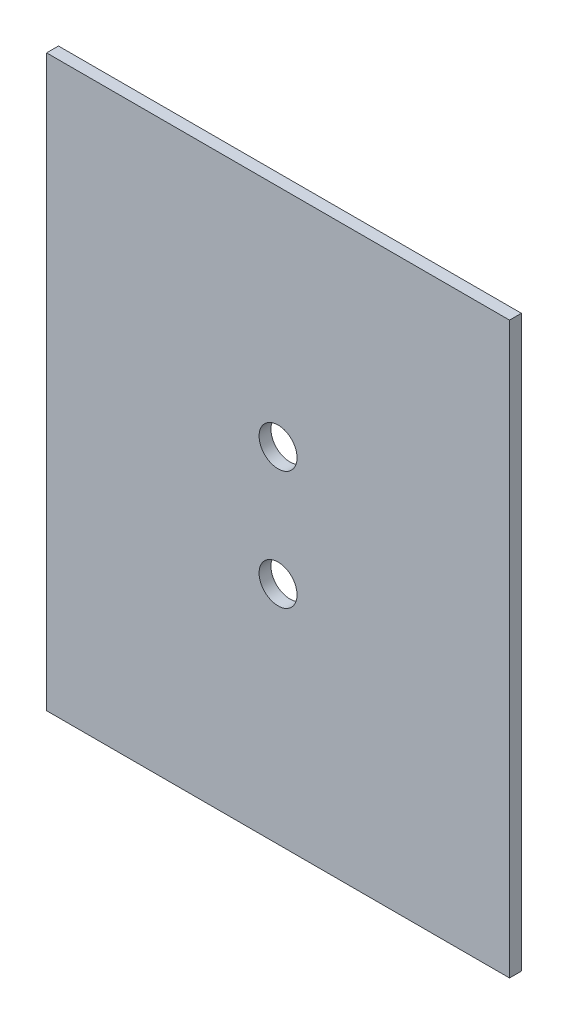
SolidWorks part; units mm, degrees
material "Pine"
ref_plane "Front Plane" through (0, 0, 0) normal (0, 0, 1) x (1, 0, 0)
ref_plane "Top Plane" through (0, 0, 0) normal (0, 1, 0) x (1, 0, 0)
ref_plane "Right Plane" through (0, 0, 0) normal (1, 0, 0) x (0, 0, -1)
sketch "Sketch1" plane through (0, 0, 0) normal (0, 0, 1) x (1, 0, 0)
  line L1 (-97.5, 120) -> (97.5, 120)
  line L2 (-97.5, 120) -> (-97.5, -120)
  line L3 (-97.5, -120) -> (97.5, -120)
  line L4 (97.5, 120) -> (97.5, -120)
  circle A0 centre (0, 25) radius 8
  circle A1 centre (0, -25) radius 8
  point P0 (0, 0)
  dimension "D3" = 16
  dimension "D1" = 195
  dimension "D2" = 240
  dimension "D4" = 50
extrude "Boss-Extrude1" add sketch "Sketch1" along normal blind 5
